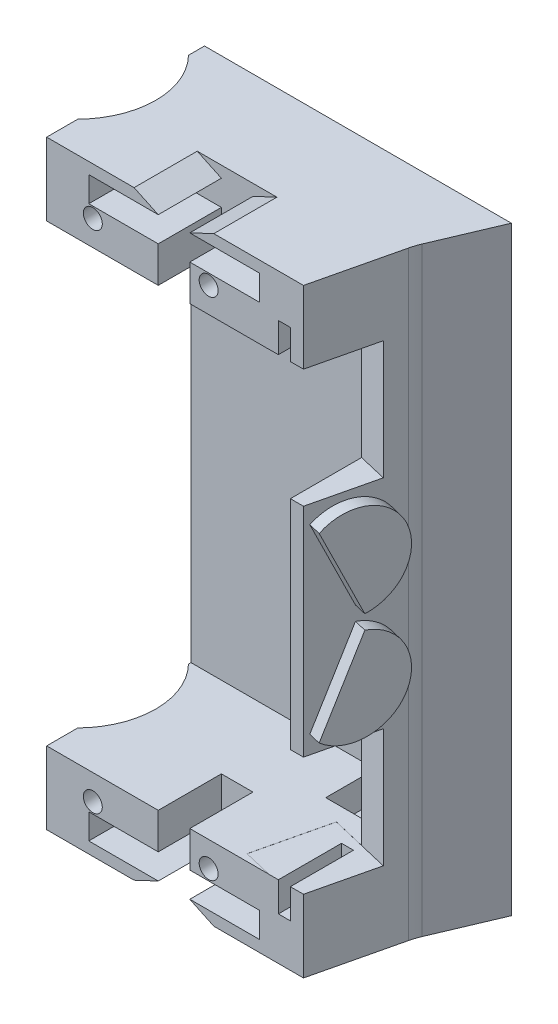
SolidWorks part; units mm, degrees
ref_plane "Alzado" through (0, 0, 0) normal (0, 0, 1) x (1, 0, 0)
ref_plane "Planta" through (0, 0, 0) normal (0, 1, 0) x (1, 0, 0)
ref_plane "Vista lateral" through (0, 0, 0) normal (1, 0, 0) x (0, 0, -1)
sketch "Croquis1" plane through (0, 0, 0) normal (0, 0, 1) x (1, 0, 0)
  line L1 (-14.1928, 14.0969) -> (32.4072, 14.0969)
  line L2 (-14.1928, 14.0969) -> (-14.1928, 2.5969)
  line L3 (-14.1928, 2.5969) -> (32.4072, 2.5969)
  line L4 (32.4072, 14.0969) -> (32.4072, 2.5969)
  line L5 (32.4072, 2.5969) -> (24.4072, 2.5969)
  line L6 (32.4072, 2.5969) -> (32.4072, -69.4031)
  line L7 (32.4072, -69.4031) -> (24.4072, -69.4031)
  line L8 (24.4072, 2.5969) -> (24.4072, -69.4031)
  line L9 (32.4072, -69.4031) -> (-14.1928, -69.4031)
  line L10 (32.4072, -69.4031) -> (32.4072, -80.9031)
  line L11 (32.4072, -80.9031) -> (-14.1928, -80.9031)
  line L12 (-14.1928, -69.4031) -> (-14.1928, -80.9031)
  dimension "D1" = 11.5
  dimension "D2" = 46.6
  dimension "D3" = 72
  dimension "0.85" = 8
  dimension "D5" = 11.5
  dimension "D6" = 46.6
extrude "Saliente-Extruir1" add sketch "Croquis1" along normal blind 25 contours L4 L1 L2 L3 | L3 L8 L7 L6 | L9 L12 L11 L10 L7
sketch "Croquis3" plane through (32.4072, 0, 0) normal (1, 0, 0) x (0, 0, -1)
  line L0 (-25, 14.0969) -> (0, 14.0969) construction
  line L1 (-45, -57.9031) -> (-15, -57.9031)
  line L2 (-45, -57.9031) -> (-45, -62.9031)
  line L3 (-45, -62.9031) -> (-15, -62.9031)
  line L4 (-15, -57.9031) -> (-15, -62.9031)
  line L5 (-45, -3.9031) -> (-15, -3.9031)
  line L6 (-45, -3.9031) -> (-45, -8.9031)
  line L7 (-45, -8.9031) -> (-15, -8.9031)
  line L8 (-15, -3.9031) -> (-15, -8.9031)
  line L9 (-25, -80.9031) -> (0, -80.9031) construction
  line L10 (0, 14.0969) -> (0, -80.9031) construction
  dimension "D1" = 5
  dimension "D2" = 30
  dimension "D3" = 5
  dimension "D4" = 30
  dimension "D5" = 18
  dimension "D6" = 18
  dimension "D7" = 15
  dimension "D8" = 15
extrude "Cortar-Extruir1" cut sketch "Croquis3" against normal blind 100
sketch "Croquis4" plane through (0, -80.9031, 0) normal (0, -1, 0) x (-1, 0, 0)
  line L0 (-32.4072, -25) -> (14.1928, -25) construction
  line L1 (-3.4796, -25) -> (-8.4796, -25)
  line L2 (-3.4796, -25) -> (-3.4796, -15)
  line L3 (-3.4796, -15) -> (-8.4796, -15)
  line L4 (-8.4796, -25) -> (-8.4796, -15)
  dimension "D1" = 10
  dimension "D2" = 5
extrude "Cortar-Extruir2" cut sketch "Croquis4" against normal blind 2000
sketch "Croquis5" plane through (0, -80.9031, 0) normal (0, -1, 0) x (1, 0, 0)
  line L0 (32.4072, 0) -> (26.4846, 25)
  line L1 (32.4072, 25) -> (8.4796, 25) construction
  line L2 (26.4846, 25) -> (32.4072, 25)
  line L3 (32.4072, 25) -> (32.4072, 0)
extrude "Cortar-Extruir3" cut sketch "Croquis5" against normal blind 2000
sketch "Croquis7" plane through (0, 14.0969, 0) normal (0, 1, 0) x (1, 0, 0)
  line L1 (-14.1928, 0) -> (24.1524, 0)
  line L2 (-14.1928, 0) -> (-14.1928, -2.151)
  line L3 (-14.1928, -2.151) -> (24.1524, -2.151)
  line L4 (24.1524, 0) -> (24.1524, -2.151)
  dimension "D1" = 2.151
  dimension "D2" = 38.3452
extrude "Saliente-Extruir2" add sketch "Croquis7" against normal blind 90
sketch "Croquis8" plane through (0, 0, 0) normal (0, 0, -1) x (-1, 0, 0)
  line L0 (-32.4072, 14.0969) -> (-32.4072, -80.9031) construction
  line L1 (-28.2072, 7.0969) -> (-15.0072, 7.0969)
  line L2 (-28.2072, 7.0969) -> (-28.2072, -2.9031)
  line L3 (-28.2072, -2.9031) -> (-15.0072, -2.9031)
  line L4 (-15.0072, 7.0969) -> (-15.0072, -2.9031)
  line L5 (-28.2072, -63.9031) -> (-15.0072, -63.9031)
  line L6 (-28.2072, -63.9031) -> (-28.2072, -73.9031)
  line L7 (-28.2072, -73.9031) -> (-15.0072, -73.9031)
  line L8 (-15.0072, -63.9031) -> (-15.0072, -73.9031)
  line L9 (14.1928, 14.0969) -> (-32.4072, 14.0969) construction
  line L10 (-32.4072, -80.9031) -> (14.1928, -80.9031) construction
  dimension "D1" = 10
  dimension "D2" = 13.2
  dimension "D3" = 10
  dimension "D4" = 13.2
  dimension "D5" = 4.2
  dimension "D6" = 7
  dimension "D7" = 7
  dimension "D8" = 4.2
extrude "Cortar-Extruir4" cut sketch "Croquis8" against normal blind 10
sketch "Croquis9" plane through (0, -80.9031, 0) normal (0, -1, 0) x (1, 0, 0)
  line L0 (32.4072, 0) -> (34.4072, 0)
  line L1 (34.4072, 0) -> (29.8716, 10.703)
  line L2 (26.4846, 25) -> (32.4072, 0) construction
  line L3 (29.8716, 10.703) -> (32.4072, 0)
  dimension "D1" = 2
extrude "Saliente-Extruir3" add sketch "Croquis9" against normal blind 95
sketch "Croquis10" plane through (0, -80.9031, 0) normal (0, -1, 0) x (1, 0, 0)
  circle A0 centre (-23.1005, 11.3078) radius 12.5
  dimension "D1" = 25
extrude "Cortar-Extruir5" cut sketch "Croquis10" against normal blind 95
sketch "Croquis11" plane through (30.685, 0, 7.2694) normal (0.9731, 0, 0.2305) x (0.2305, 0, -0.9731)
  line L0 (-11.3789, -34.5255) -> (-17.3906, -47.7781)
  line L1 (-11.3789, -32.2806) -> (-17.3906, -19.028)
  line L4 (-7.9446, -57.9031) -> (-18.2213, -57.9031) construction
  line L6 (-3.5287, 14.0969) -> (-3.5287, -80.9031) construction
  arc A0 (-17.3906, -47.7781) -> (-11.3789, -34.5255) centre (-12.7287, -41.9031) ccw
  arc A1 (-11.3789, -32.2806) -> (-17.3906, -19.028) centre (-12.7287, -24.9031) ccw
  dimension "D1" = 15
  dimension "D2" = 16
  dimension "D3" = 17
  dimension "D4" = 9.2
  dimension "D5" = 9.2
extrude "Saliente-Extruir4" add sketch "Croquis11" along normal blind 2
fillet "Redondeo1" radius 10 1 edges at (29.8716, -33.4031, 10.703)
sketch "Croquis13" plane through (0, 0, 0) normal (0, 0, -1) x (-1, 0, 0)
  circle A0 centre (-18.8072, -77.9031) radius 1.5
  circle A1 centre (1.8928, -77.9031) radius 1.5
  circle A2 centre (-29.5601, -45.1031) radius 1.5
  circle A3 centre (-29.5601, -21.7031) radius 1.5
  circle A4 centre (-18.8072, 11.0969) radius 1.5
  circle A5 centre (1.8928, 11.0969) radius 1.5
extrude "Cortar-Extruir7" cut sketch "Croquis13" against normal blind 5
sketch "Croquis16" plane through (30.685, 0, 7.2694) normal (0.9731, 0, 0.2305) x (0.2305, 0, -0.9731)
  line L1 (-19.4821, -69.4139) -> (-7.7213, -69.4139)
  line L2 (-19.4821, -69.4139) -> (-19.4821, -50.6139)
  line L3 (-19.4821, -50.6139) -> (-7.7213, -50.6139)
  line L4 (-7.7213, -69.4139) -> (-7.7213, -50.6139)
  line L5 (-18.2213, -33.4031) -> (7.9317, -33.4031) construction
  line L6 (-18.2213, -8.9031) -> (-18.2213, -57.9031) construction
  line L7 (7.9317, 14.0969) -> (7.9317, -80.9031) construction
  line L8 (-19.4821, 2.6078) -> (-19.4821, -16.1922)
  line L9 (-19.4821, 2.6078) -> (-7.7213, 2.6078)
  line L10 (-7.7213, 2.6078) -> (-7.7213, -16.1922)
  line L11 (-19.4821, -16.1922) -> (-7.7213, -16.1922)
  dimension "D1" = 18.8
extrude "Cortar-Extruir9" cut sketch "Croquis16" against normal blind 10
sketch "Croquis17" plane through (0, 0, 25) normal (0, 0, 1) x (1, 0, 0)
  line L0 (24.4072, -69.4031) -> (24.4072, -74.1031)
  line L1 (24.4072, -74.1031) -> (22.5072, -74.1031)
  line L2 (22.5072, -74.1031) -> (22.5072, -69.4139)
  line L3 (21.0154, -69.4139) -> (26.4846, -69.4139) construction
  line L4 (22.5072, -69.4139) -> (24.4072, -69.4031)
  line L5 (26.4846, -33.4031) -> (-15.6804, -33.4031) construction
  line L6 (26.4846, -16.1922) -> (26.4846, -50.6139) construction
  line L7 (22.5072, 2.6078) -> (24.4072, 2.5969)
  line L8 (24.4072, 2.5969) -> (24.4072, 7.2969)
  line L9 (24.4072, 7.2969) -> (22.5072, 7.2969)
  line L10 (22.5072, 7.2969) -> (22.5072, 2.6078)
  dimension "D1" = 1.9
  dimension "D2" = 4.7
extrude "Cortar-Extruir10" cut sketch "Croquis17" against normal blind 10
sketch "Croquis18" plane through (0, 0, 25) normal (0, 0, 1) x (1, 0, 0)
  line L0 (-14.1928, 14.0969) -> (3.4796, 14.0969) construction
  line L1 (-7.5204, 12.2969) -> (19.4796, 12.2969)
  line L2 (-7.5204, 12.2969) -> (-7.5204, 8.2969)
  line L3 (-7.5204, 8.2969) -> (19.4796, 8.2969)
  line L4 (19.4796, 12.2969) -> (19.4796, 8.2969)
  line L5 (3.4796, 14.0969) -> (3.4796, 2.5969) construction
  line L6 (3.4796, 12.2969) -> (-0.3416, 14.0969)
  line L7 (3.4796, 14.0969) -> (3.4796, 2.5969) construction
  line L8 (8.4571, 12.2969) -> (12.2782, 14.0969)
  line L9 (8.4796, 14.0969) -> (26.4846, 14.0969) construction
  line L10 (-0.3416, 14.0969) -> (3.4796, 14.0969)
  line L11 (3.4796, 14.0969) -> (3.4796, 12.2969)
  line L12 (12.2782, 14.0969) -> (8.4796, 14.0969)
  line L13 (8.4796, 14.0969) -> (8.4796, 2.5969) construction
  line L14 (8.4796, 14.0969) -> (8.4796, 2.5969) construction
  line L15 (8.4796, 14.0969) -> (8.4571, 12.2969)
  line L16 (26.4846, -33.4031) -> (-14.1928, -33.4031) construction
  line L17 (26.4846, -16.1922) -> (26.4846, -50.6139) construction
  line L18 (-14.1928, -69.4031) -> (-14.1928, 2.5969) construction
  line L19 (8.4571, -79.1031) -> (12.2782, -80.9031)
  line L20 (12.2782, -80.9031) -> (8.4796, -80.9031)
  line L21 (8.4796, -80.9031) -> (8.4571, -79.1031)
  line L22 (3.4796, -80.9031) -> (3.4796, -79.1031)
  line L23 (-0.3416, -80.9031) -> (3.4796, -80.9031)
  line L24 (3.4796, -79.1031) -> (-0.3416, -80.9031)
  line L25 (-7.5204, -79.1031) -> (-7.5204, -75.1031)
  line L26 (19.4796, -79.1031) -> (19.4796, -75.1031)
  line L27 (-7.5204, -79.1031) -> (19.4796, -79.1031)
  line L28 (-7.5204, -75.1031) -> (19.4796, -75.1031)
  line M3 (3.4796, -80.9031) -> (3.4796, -69.4031)
  line M6 (-14.1928, -80.9031) -> (3.4796, -80.9031)
  dimension "D1" = 4
  dimension "D2" = 27
  dimension "D3" = 1.8
  dimension "D4" = 11
extrude "Cortar-Extruir11" cut sketch "Croquis18" against normal blind 10 contours L24 M3 M6 | L21 L20 L19 | L4 L1 L2 L3 | L12 L15 L8 | L27 L26 L28 L25 | L6 L10 L11
sketch "Croquis20" plane through (0, 0, 25) normal (0, 0, 1) x (1, 0, 0)
  line L0 (24.4072, -33.4031) -> (-14.1928, -33.4031) construction
  line L1 (24.4072, -16.1922) -> (24.4072, -50.6139) construction
  line L2 (-14.1928, -69.4031) -> (-14.1928, 2.5969) construction
  line L3 (-14.1928, 14.0969) -> (-14.1928, 2.5969) construction
  line L4 (26.4846, -80.9031) -> (12.2782, -80.9031) construction
  line L5 (26.4846, 14.0969) -> (26.4846, 2.6078) construction
  line L6 (12.2782, 14.0969) -> (-0.3416, 14.0969) construction
  line L7 (12.2782, 14.0969) -> (26.4846, 14.0969) construction
  circle A0 centre (11.4637, -73.4031) radius 1.5
  circle A1 centre (-6.8811, -73.4031) radius 1.5
  circle A2 centre (11.4637, 6.5969) radius 1.5
  circle A3 centre (-6.8811, 6.5969) radius 1.5
  dimension "D1" = 3
  dimension "D2" = 3
  dimension "D3" = 7.5
extrude "Cortar-Extruir12" cut sketch "Croquis20" against normal blind 10
